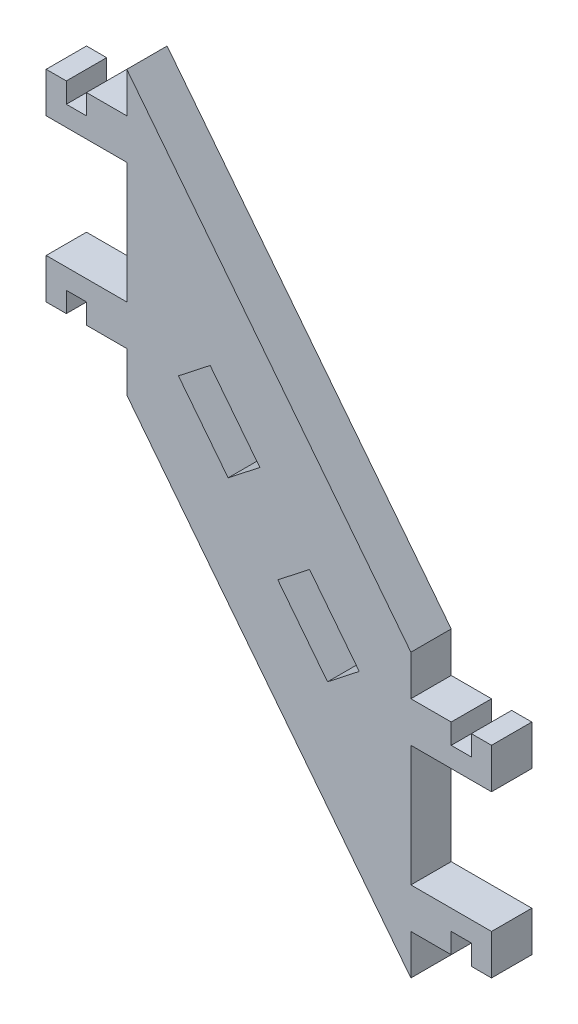
SolidWorks part; units mm, degrees
ref_plane "Front Plane" through (0, 0, 0) normal (0, 0, 1) x (1, 0, 0)
ref_plane "Top Plane" through (0, 0, 0) normal (0, 1, 0) x (1, 0, 0)
ref_plane "Right Plane" through (0, 0, 0) normal (1, 0, 0) x (0, 0, -1)
sketch "Sketch1" plane through (0, 0, 0) normal (0, 0, 1) x (1, 0, 0)
  line L0 (-44.7548, 79.375) -> (-44.7548, 73.025)
  line L1 (-44.7548, 34.925) -> (0, -22.225)
  line L2 (0, -22.225) -> (0, -15.875)
  line L3 (0, 22.225) -> (-44.7548, 79.375)
  line L4 (-44.7548, 73.025) -> (-51.1048, 73.025)
  line L5 (-57.4548, 73.025) -> (-57.4548, 66.675)
  line L6 (-57.4548, 66.675) -> (-44.7548, 66.675)
  line L7 (-44.7548, 79.375) -> (-51.1048, 79.375) construction
  line L8 (-51.1048, 79.375) -> (-51.1048, 34.925) construction
  line L9 (-51.1048, 34.925) -> (-44.7548, 34.925) construction
  line L10 (-54.2798, 73.025) -> (-54.2798, 69.8413)
  line L11 (-54.2798, 69.8413) -> (-51.1048, 69.8413)
  line L12 (-51.1048, 69.8413) -> (-51.1048, 73.025)
  line L13 (-54.2798, 73.025) -> (-57.4548, 73.025)
  line L14 (-44.7548, 57.15) -> (-64.1486, 57.15) construction
  line L15 (-44.7548, 41.275) -> (-51.1048, 41.275)
  line L16 (-57.4548, 47.625) -> (-44.7548, 47.625)
  line L17 (-54.2798, 41.275) -> (-57.4548, 41.275)
  line L18 (-51.1048, 44.4587) -> (-51.1048, 41.275)
  line L19 (-54.2798, 44.4587) -> (-51.1048, 44.4587)
  line L20 (-54.2798, 41.275) -> (-54.2798, 44.4587)
  line L21 (-57.4548, 41.275) -> (-57.4548, 47.625)
  line L22 (-57.4548, 69.85) -> (-51.1048, 69.85) construction
  line L23 (0, 0) -> (19.05, 0) construction
  line L24 (0, 9.525) -> (12.7, 9.525)
  line L25 (12.7, 9.525) -> (12.7, 15.875)
  line L26 (12.7, 15.875) -> (9.525, 15.875)
  line L27 (9.525, 15.875) -> (9.525, 12.6913)
  line L28 (9.525, 12.6913) -> (6.35, 12.6913)
  line L29 (6.35, 12.6913) -> (6.35, 15.875)
  line L30 (6.35, 15.875) -> (0, 15.875)
  line L31 (6.35, -15.875) -> (0, -15.875)
  line L32 (6.35, -12.6913) -> (6.35, -15.875)
  line L33 (9.525, -12.6913) -> (6.35, -12.6913)
  line L34 (9.525, -15.875) -> (9.525, -12.6913)
  line L35 (12.7, -15.875) -> (9.525, -15.875)
  line L36 (12.7, -9.525) -> (12.7, -15.875)
  line L37 (0, -9.525) -> (12.7, -9.525)
  line L38 (0, 22.225) -> (6.35, 22.225) construction
  line L39 (6.35, 22.225) -> (6.35, -22.225) construction
  line L40 (6.35, -22.225) -> (0, -22.225) construction
  line L42 (-44.7548, 66.675) -> (-44.7548, 47.625)
  line L43 (-44.7548, 41.275) -> (-44.7548, 34.925)
  line L44 (0, 15.875) -> (0, 22.225)
  line L45 (0, -9.525) -> (0, 9.525)
  point P37 (0, 0)
  dimension "D1" = 44.7548
  dimension "D2" = 101.6
  dimension "D4" = 6.35
  dimension "D5" = 3.175
  dimension "D6" = 6.35
  dimension "D7" = 19.05
  dimension "D8" = 44.45
  dimension "D3" = 19.05
  dimension "D10" = 6.35
  dimension "D11" = 6.35
  dimension "D12" = 3.175
  dimension "D13" = 31.75
  dimension "D14" = 3.175
  dimension "D15" = 25.3826
  dimension "D16" = 3.1663
  dimension "D9" = 3.175
  dimension "D17" = 3.1663
  dimension "D18" = 3.175
extrude "Profile" add sketch "Sketch1" along normal blind 6.35 contours L1 L2 L31 L32 L33 L34 L35 L36 L37 L45 L24 L25 L26 L27 L28 L29 L30 L44 L3 L0 L4 L12 L11 L10 L13 L5 L6 L42 L16 L21 L17 L20 L19 L18 L15 L43
sketch "Sketch2" plane through (0, 0, 6.35) normal (0, 0, 1) x (1, 0, 0)
  line L0 (-44.7548, 57.15) -> (0, 0) construction
  line L1 (-44.7548, 66.675) -> (-44.7548, 47.625) construction
  line L2 (-31.623, 45.5309) -> (-36.6225, 41.6158)
  line L3 (-36.6225, 41.6158) -> (-28.7922, 31.6169)
  line L4 (-28.7922, 31.6169) -> (-23.7928, 35.532)
  line L5 (-23.7928, 35.532) -> (-31.623, 45.5309)
  line L6 (-33.1659, 20.1264) -> (-11.5889, 37.0236) construction
  line L7 (0, 22.225) -> (-44.7548, 79.375) construction
  line L8 (-15.9626, 25.5331) -> (-8.1323, 15.5342)
  line L9 (-20.962, 21.618) -> (-15.9626, 25.5331)
  line L10 (-13.1318, 11.6191) -> (-20.962, 21.618)
  line L11 (-8.1323, 15.5342) -> (-13.1318, 11.6191)
  point P7 (-34.1227, 43.5733)
  point P14 (-22.3774, 28.575)
  dimension "D1" = 6.35
  dimension "D2" = 12.7
  dimension "D3" = 6.35
extrude "Cut-Extrude1" cut sketch "Sketch2" against normal through all
equation "\"D3@Sketch1\"=\"D7@Sketch1\""
equation "\"D10@Sketch1\"=\"D6@Sketch1\""
equation "\"D12@Sketch1\"=\"D5@Sketch1\""
equation "\"D17@Sketch1\"=\"D16@Sketch1\""
equation "\"D18@Sketch1\"=\"D9@Sketch1\""
